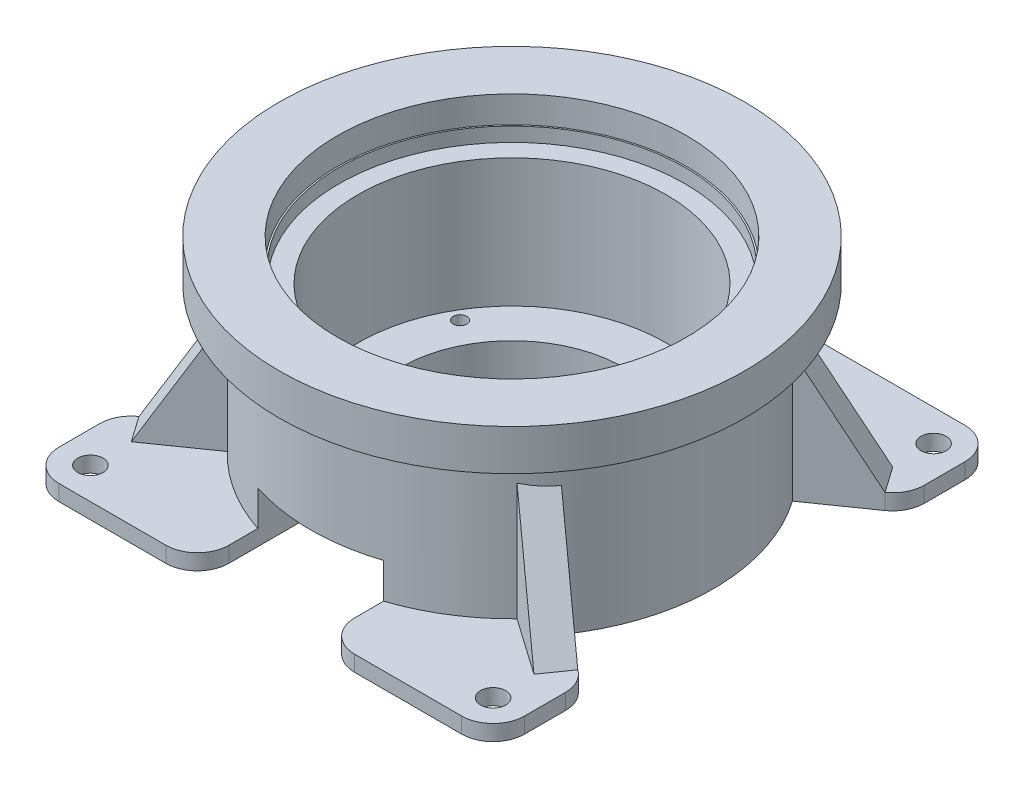
SolidWorks part; units mm, degrees
ref_plane "前视基准面" through (0, 0, 0) normal (0, 0, 1) x (1, 0, 0)
ref_plane "上视基准面" through (0, 0, 0) normal (0, 1, 0) x (1, 0, 0)
ref_plane "右视基准面" through (0, 0, 0) normal (1, 0, 0) x (0, 0, -1)
sketch "草图1" plane through (0, 0, 0) normal (0, 1, 0) x (1, 0, 0)
  circle A0 centre (0, 0) radius 64
  circle A1 centre (0, 0) radius 49
extrude "凸台-拉伸1" add sketch "草图1" along normal blind 52
sketch "草图13" plane through (0, 0, 0) normal (0, -1, 0) x (1, 0, 0)
  circle A0 centre (0, 0) radius 49
  circle A1 centre (0, 0) radius 35.5
extrude "凸台-拉伸3" add sketch "草图13" against normal blind 11.2
sketch "草图16" plane through (0, 0, 0) normal (0, -1, 0) x (1, 0, 0)
  line L4 (38.9709, -21.4104) -> (38.9709, -22.5004) construction
  line L6 (38.9709, -22.5004) -> (0, 0) construction
  line L7 (0, 0) -> (-38.9709, 22.5004) construction
  line L12 (38.3313, 33.5681) -> (38.3313, 23.5735) construction
  line L14 (38.3313, 23.5735) -> (38.3313, 22.4835) construction
  line L18 (38.3313, 22.4835) -> (39.1744, 22.4835) construction
  line L20 (38.978, 22.4835) -> (0, 0) construction
  line L21 (0, 0) -> (-38.98, -22.4846) construction
  arc A0 (-1.2467, 44.9827) -> (38.9709, -22.5004) centre (0, 0) cw construction
  arc A1 (-1.2467, 44.9827) -> (-38.9709, 22.5004) centre (0, 0) ccw construction
  arc A2 (-38.98, -22.4846) -> (-38.9709, 22.5004) centre (0, 0) cw construction
  point P25 (38.9709, -22.5004)
  point P41 (-38.9709, 22.5004)
  point P103 (38.978, 22.4835)
  point P128 (-38.98, -22.4846)
hole_wizard "M4 六角圆柱头螺钉的柱形沉头孔11" positions "草图16" profile "草图17" counterbore size "M4" standard "GB" end condition through all
sketch "草图17" plane through (-38.98, 0, -22.4846) normal (1, 0, 0) x (0, 0, -1)
  line L0 (0, 0) -> (0, 52)
  line L1 (0, 52) -> (2.15, 52)
  line L3 (2.15, 52) -> (2.15, 4.6)
  line L4 (2.15, 4.6) -> (4, 4.6)
  line L5 (4, 4.6) -> (4, 0)
  line L7 (4, 0) -> (0, 0)
  line L11 (0, -6.35) -> (0, 107.95) construction
  dimension "通孔孔直径" = 4.3
  dimension "通孔孔深度" = 52
  dimension "柱形沉头孔直径" = 8
  dimension "柱形沉头孔深度" = 4.6
sketch "草图18" plane through (0, 52, 0) normal (0, 1, 0) x (1, 0, 0)
  circle A0 centre (0, 0) radius 74
  circle A1 centre (0, 0) radius 56
extrude "凸台-拉伸4" add sketch "草图18" along normal blind 13
sketch "草图25" plane through (0, 0, 0) normal (0, -1, 0) x (1, 0, 0)
  line L0 (-74, 57.021) -> (-74, 70)
  line L1 (-64, 80) -> (64, 80)
  line L2 (74, 70) -> (74, 57.021)
  line L3 (-52.4257, 36.7089) -> (-69.7358, 48.8295)
  line L4 (52.4257, 36.7089) -> (69.7358, 48.8295)
  arc A1 (-74, 70) -> (-64, 80) centre (-64, 70) cw
  arc A2 (74, 70) -> (64, 80) centre (64, 70) ccw
  arc A3 (-74, 57.021) -> (-69.7358, 48.8295) centre (-64, 57.021) ccw
  arc A4 (74, 57.021) -> (69.7358, 48.8295) centre (64, 57.021) cw
  arc A5 (-52.4257, 36.7089) -> (52.4257, 36.7089) centre (0, 0) cw
  circle A6 centre (0, 0) radius 64 construction
  circle A7 centre (-64, 70) radius 4
  circle A8 centre (64, 70) radius 4
  point P8 (-74, 80)
  point P11 (74, 80)
  dimension "D3" = 10
  dimension "D4" = 10
  dimension "D1" = 10
  dimension "D2" = 10
extrude "凸台-拉伸7" add sketch "草图25" against normal blind 5
sketch "草图28" plane through (0, 0, 0) normal (0, -1, 0) x (1, 0, 0)
  line L0 (-52.4257, -36.7089) -> (-69.7358, -48.8295)
  line L2 (-74, -57.021) -> (-74, -70)
  line L3 (-64, -80) -> (64, -80)
  line L4 (74, -57.021) -> (74, -70)
  line L5 (43.4587, -46.9824) -> (74, -80) construction
  line L6 (-74, -80) -> (-43.4587, -46.9824) construction
  line L7 (52.4257, -36.7089) -> (69.7358, -48.8295)
  arc A0 (-64, -80) -> (-74, -70) centre (-64, -70) cw
  arc A1 (74, -70) -> (64, -80) centre (64, -70) cw
  arc A2 (-52.4257, -36.7089) -> (52.4257, -36.7089) centre (0, 0) ccw
  circle A3 centre (0, 0) radius 64 construction
  arc A4 (-74, -57.021) -> (-69.7358, -48.8295) centre (-64, -57.021) cw
  arc A5 (74, -57.021) -> (69.7358, -48.8295) centre (64, -57.021) ccw
  circle A6 centre (-64, -70) radius 4
  circle A7 centre (64, -70) radius 4
  point P0 (0, 0)
  dimension "D3" = 10
  dimension "D4" = 10
  dimension "D1" = 10
  dimension "D5" = 10
  dimension "D2" = 148
extrude "凸台-拉伸8" add sketch "草图28" against normal blind 5
sketch "草图14" plane through (0, 0, 0) normal (0, 0, 1) x (1, 0, 0)
  line L0 (0, 0) -> (20, 0)
  line L1 (-64, 0) -> (64, 0) construction
  line L2 (20, 0) -> (20, 16.2)
  line L3 (20, 16.2) -> (-20, 16.2)
  line L4 (-20, 16.2) -> (-20, 0)
  line L5 (-20, 0) -> (0, 0)
  dimension "D1" = 20
  dimension "D2" = 16.2
  dimension "D4" = 20
extrude "切除-拉伸2" cut sketch "草图14" along normal blind 81
sketch "草图27" plane through (0, 0, 0) normal (0, -1, 0) x (1, 0, 0)
  line L0 (0, 0) -> (-34.6482, 34.6482)
  line L2 (34.6482, 34.6482) -> (0, 0)
  arc A0 (34.6482, 34.6482) -> (-34.6482, 34.6482) centre (0, 0) ccw
fillet "圆角4" radius 10 1 edges at (-20, 2.5, 80)
fillet "圆角5" radius 10 1 edges at (20, 2.5, 80)
sketch "草图32" plane through (0, 0, 0) normal (0.5736, 0, -0.8192) x (-0.8192, 0, -0.5736)
  line L0 (-64, 41) -> (-64, 5) construction
  line L1 (-64, 52) -> (-64, 5) construction
  line L2 (-85.1316, 5) -> (-64, 41)
rib "筋1" sketch "草图32" sketch "草图32" thickness 10 extrusion direction parallel to sketch draft on no parameters "D1"=10
sketch "草图33" plane through (0, 0, 0) normal (-0.5736, 0, -0.8192) x (-0.8192, 0, 0.5736)
  line L0 (64, 5) -> (64, 41) construction
  line L1 (64, 5) -> (64, 52) construction
  line L2 (64, 41) -> (85.1316, 5)
rib "筋2" sketch "草图33" sketch "草图33" thickness 10 extrusion direction parallel to sketch draft on no parameters "D1"=10
sketch "草图34" plane through (0, 0, 0) normal (-0.5736, 0, 0.8192) x (0.8192, 0, 0.5736)
  line L0 (-64, 5) -> (-64, 41) construction
  line L1 (-64, 52) -> (-64, 5) construction
  line L2 (-85.1316, 5) -> (-64, 41)
rib "筋7" sketch "草图34" sketch "草图34" thickness 10 extrusion direction parallel to sketch draft on no parameters "D1"=10
sketch "草图35" plane through (0, 0, 0) normal (0.5736, 0, 0.8192) x (0.8192, 0, -0.5736)
  line L0 (64, 5) -> (64, 41) construction
  line L1 (64, 5) -> (64, 52) construction
  line L2 (64, 41) -> (85.1316, 5)
rib "筋9" sketch "草图35" sketch "草图35" thickness 10 extrusion direction parallel to sketch draft on no parameters "D1"=10
sketch "草图36" plane through (0, 52, 0) normal (0, 1, 0) x (1, 0, 0)
  circle A0 centre (0, 0) radius 56
  circle A1 centre (0, 0) radius 55
extrude "凸台-拉伸9" add sketch "草图36" along normal up to surface (13 mm away) up to face at (0, 65, 56)
sketch "草图37" plane through (0, 65, 0) normal (0, 1, 0) x (1, 0, 0)
  circle A0 centre (0, 0) radius 55.5
extrude "切除-拉伸3" cut sketch "草图37" against normal blind 8.5
